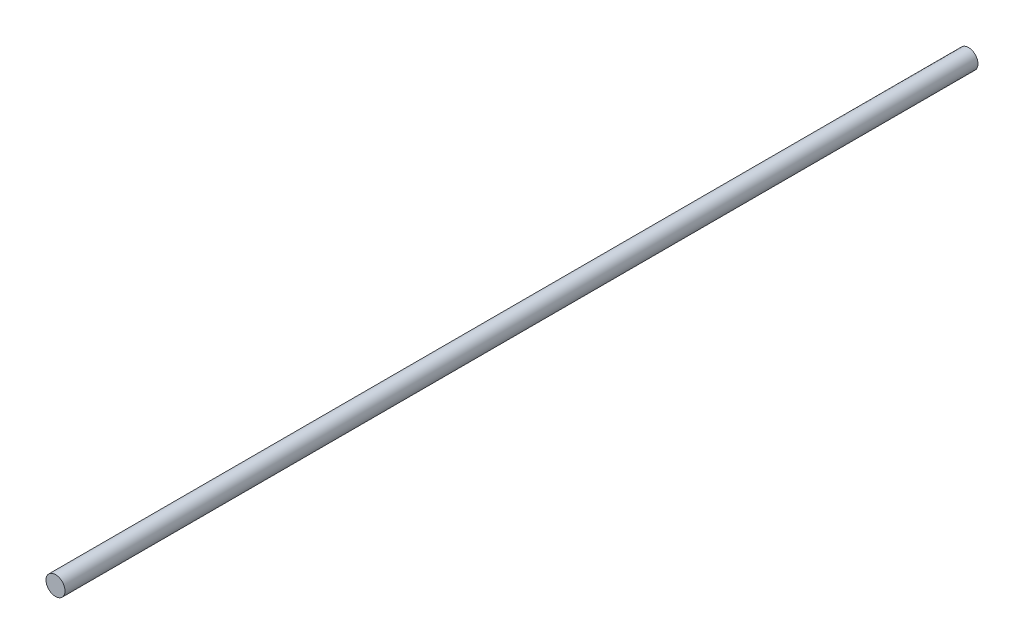
SolidWorks part; units mm, degrees
ref_plane "前视基准面" through (0, 0, 0) normal (0, 0, 1) x (1, 0, 0)
ref_plane "上视基准面" through (0, 0, 0) normal (0, 1, 0) x (1, 0, 0)
ref_plane "右视基准面" through (0, 0, 0) normal (1, 0, 0) x (0, 0, -1)
sketch "草图1" plane through (0, 0, 0) normal (0, 0, 1) x (1, 0, 0)
  circle A0 centre (0, 0) radius 4
  dimension "D1" = 8
extrude "凸台-拉伸1" add sketch "草图1" along normal blind 384
